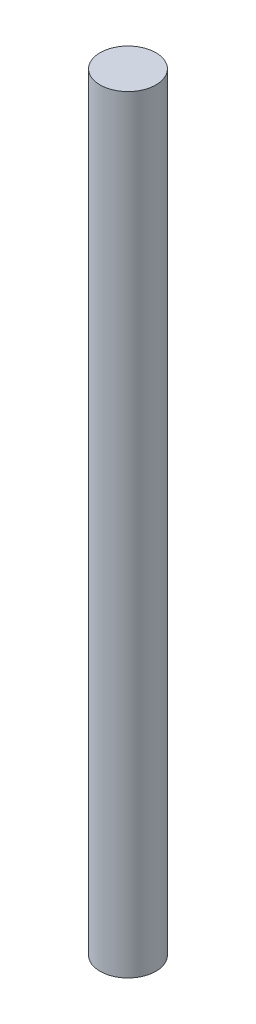
SolidWorks part; units mm, degrees
ref_plane "Front Plane" through (0, 0, 0) normal (0, 0, 1) x (1, 0, 0)
ref_plane "Top Plane" through (0, 0, 0) normal (0, 1, 0) x (1, 0, 0)
ref_plane "Right Plane" through (0, 0, 0) normal (1, 0, 0) x (0, 0, -1)
sketch "Sketch1" plane through (0, 0, 0) normal (0, 1, 0) x (1, 0, 0)
  circle A0 centre (0, 0) radius 4
  dimension "D1" = 8
extrude "Boss-Extrude1" add sketch "Sketch1" along normal blind 110
